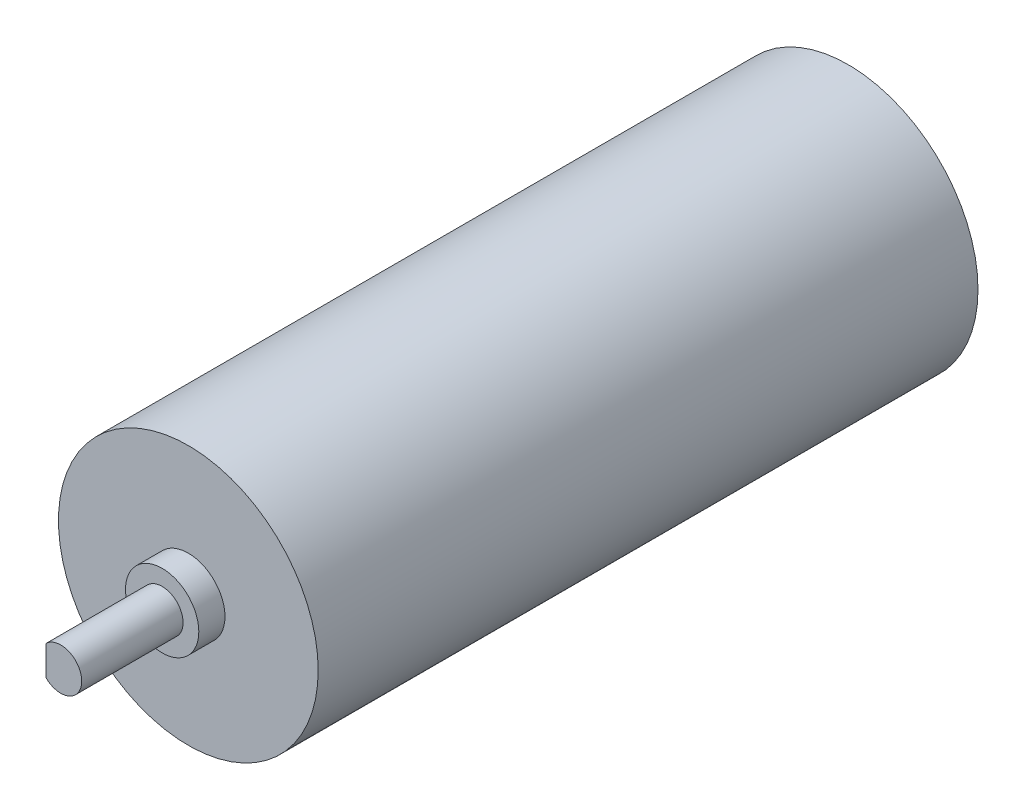
SolidWorks part; units mm, degrees
ref_plane "前视基准面" through (0, 0, 0) normal (0, 0, 1) x (1, 0, 0)
ref_plane "上视基准面" through (0, 0, 0) normal (0, 1, 0) x (1, 0, 0)
ref_plane "右视基准面" through (0, 0, 0) normal (1, 0, 0) x (0, 0, -1)
sketch "草图1" plane through (0, 0, 0) normal (0, 0, 1) x (1, 0, 0)
  circle A0 centre (0, 0) radius 12.4
  dimension "D1" = 24.8
extrude "凸台-拉伸1" add sketch "草图1" along normal blind 63
sketch "草图2" plane through (0, 0, 63) normal (0, 0, 1) x (1, 0, 0)
  circle A0 centre (0, 0) radius 3.5
  dimension "D1" = 7
extrude "凸台-拉伸2" add sketch "草图2" along normal blind 2.5
sketch "草图3" plane through (0, 0, 65.5) normal (0, 0, 1) x (1, 0, 0)
  line L0 (-1.41, 1.4184) -> (-1.41, -1.4184)
  arc A0 (-1.41, -1.4184) -> (-1.41, 1.4184) centre (0, 0) ccw
  dimension "D1" = 4
  dimension "D2" = 1.41
extrude "凸台-拉伸3" add sketch "草图3" along normal blind 9.68
